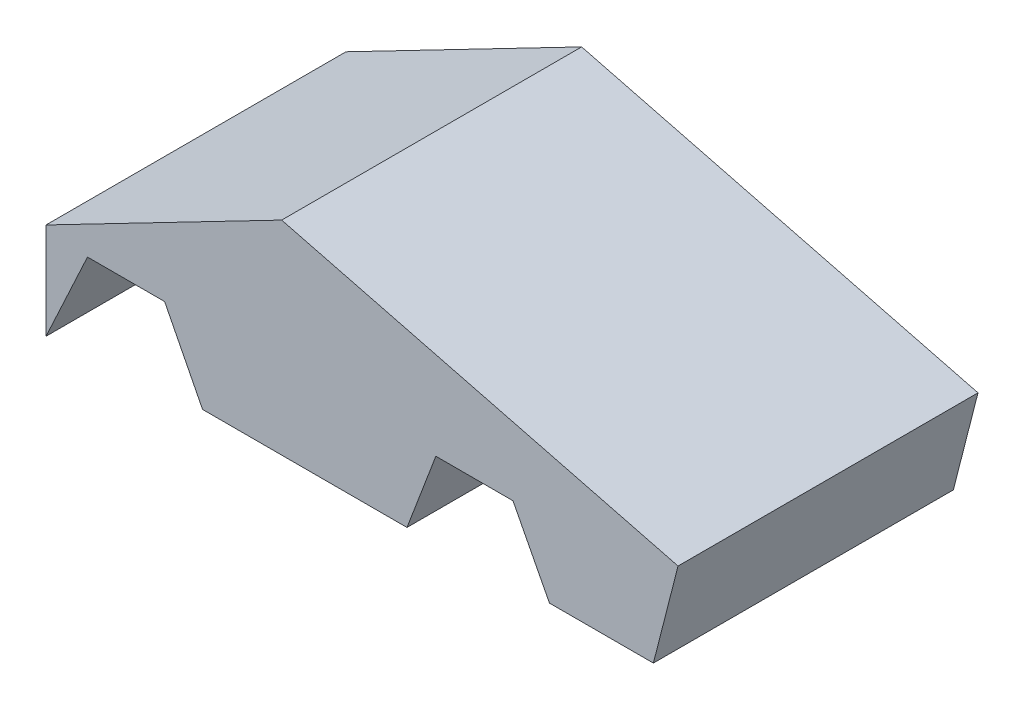
SolidWorks part; units mm, degrees
ref_plane "Front Plane" through (0, 0, 0) normal (0, 0, 1) x (1, 0, 0)
ref_plane "Top Plane" through (0, 0, 0) normal (0, 1, 0) x (1, 0, 0)
ref_plane "Right Plane" through (0, 0, 0) normal (1, 0, 0) x (0, 0, -1)
sketch "Sketch1" plane through (0, 0, 0) normal (0, 0, 1) x (1, 0, 0)
  line L0 (104.4317, 46.1824) -> (-5.5683, -10.7911)
  line L1 (104.4317, 46.1824) -> (289.4317, -1.1444)
  line L2 (289.4317, -1.1444) -> (277.9197, -46.1444)
  line L3 (212.3915, -13.2897) -> (229.4083, -46.1444)
  line L4 (-5.5683, -55.7911) -> (13.8016, -14.0682)
  line L5 (13.8016, -14.0682) -> (49.8016, -14.0682)
  line L6 (49.8016, -14.0682) -> (67.5016, -48.8203)
  line L7 (67.5016, -48.8203) -> (162.9164, -48.8203)
  line L8 (162.9164, -48.8203) -> (176.3915, -13.2897)
  line L9 (176.3915, -13.2897) -> (212.3915, -13.2897)
  line L10 (229.4083, -46.1444) -> (277.9197, -46.1444)
  line L11 (-5.5683, -10.7911) -> (-5.5683, -55.7911)
  point P5 (84.7437, 35.0012)
  point P6 (0, 0)
  point P12 (0, 0)
  point P13 (0, 0)
  point P15 (244.6621, -49.9799)
  point P17 (99.5575, 26.3598)
  point P18 (103.9635, 46.4029)
  point P19 (0, 0)
  dimension "D2" = 110
  dimension "D3" = 45
  dimension "D4" = 46
  dimension "D5" = 36
  dimension "D6" = 39
  dimension "D7" = 36
  dimension "D8" = 38
  dimension "D9" = 45
  dimension "D10" = 185
  dimension "D11" = 37
extrude "Boss-Extrude1" add sketch "Sketch1" along normal blind 140
